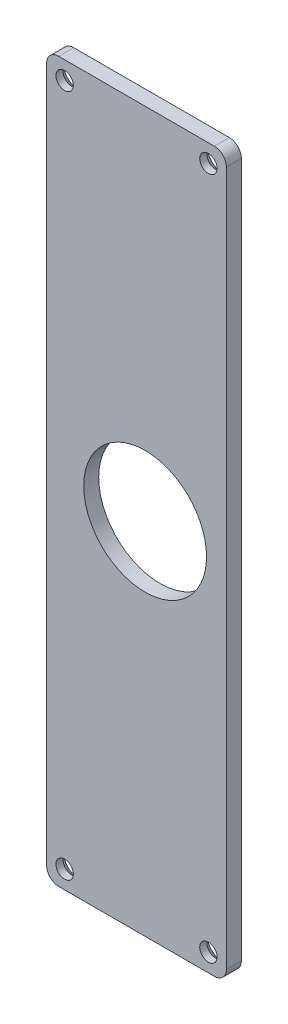
SolidWorks part; units mm, degrees
ref_plane "Front Plane" through (0, 0, 0) normal (0, 0, 1) x (1, 0, 0)
ref_plane "Top Plane" through (0, 0, 0) normal (0, 1, 0) x (1, 0, 0)
ref_plane "Right Plane" through (0, 0, 0) normal (1, 0, 0) x (0, 0, -1)
sketch "Sketch1" plane through (0, 0, 0) normal (0, 0, 1) x (1, 0, 0)
  line L0 (-63.1226, 90.4321) -> (-63.1226, -25.5679)
  line L1 (-91.1226, -27.5679) -> (-65.1226, -27.5679)
  line L2 (-93.1226, -25.5679) -> (-93.1226, 90.4321)
  line L3 (-91.1226, 92.4321) -> (-65.1226, 92.4321)
  arc A0 (-91.1226, -27.5679) -> (-93.1226, -25.5679) centre (-91.1226, -25.5679) cw
  arc A3 (-93.1226, 90.4321) -> (-91.1226, 92.4321) centre (-91.1226, 90.4321) cw
  arc A6 (-65.1226, 92.4321) -> (-63.1226, 90.4321) centre (-65.1226, 90.4321) cw
  arc A7 (-65.1226, -27.5679) -> (-63.1226, -25.5679) centre (-65.1226, -25.5679) ccw
  point P6 (-93.1226, -27.5679)
  point P23 (-63.1226, 92.4321)
  point P26 (-63.1226, -27.5679)
  dimension "D3" = 2
  dimension "D1" = 116
  dimension "D2" = 26
extrude "Boss-Extrude1" add sketch "Sketch1" along normal blind 2.5
hole_wizard "CSK for M2.5 Countersunk Flat Head Screw2" positions "3DSketch2" profile "Sketch3" countersink size "M2.5" standard "ISO" end condition through all
sketch3d "3DSketch2"
  line L0 (-65.1226, 92.4321, 0) -> (-91.1226, 92.4321, 0) construction
  line L2 (-93.1226, 90.4321, 0) -> (-93.1226, -25.5679, 0) construction
  line L4 (-91.1226, -27.5679, 0) -> (-65.1226, -27.5679, 0) construction
  line L5 (-63.1226, -25.5679, 0) -> (-63.1226, 90.4321, 0) construction
  point P0 (-66.1226, 89.4321, 0)
  point P2 (-90.1226, 89.4321, 0)
  point P4 (-66.1226, -24.5679, 0)
  point P6 (-90.1226, -24.5679, 0)
  dimension "D1" = 3
  dimension "D2" = 3
  dimension "D3" = 3
  dimension "D4" = 3
sketch "Sketch3" plane through (-66.1226, 89.4321, 0) normal (1, 0, 0) x (0, 1, 0)
  line L0 (0, 0) -> (0, 2.5)
  line L1 (0, 2.5) -> (1.45, 2.5)
  line L2 (1.45, 2.5) -> (1.45, 1.3)
  line L3 (1.45, 1.3) -> (2.75, 0)
  line L5 (2.75, 0) -> (0, 0)
  line L6 (-1.45, 1.3) -> (-2.75, 0) construction
  line L11 (0, -6.35) -> (0, 107.95) construction
  dimension "Thru Hole Dia." = 2.9
  dimension "Thru Hole Depth" = 2.5
  dimension "Near C'Sink Dia." = 5.5
  dimension "Near C'Sink Angle" = 90
sketch "Sketch4" plane through (0, 0, 0) normal (0, 0, -1) x (-1, 0, 0)
  line L0 (93.1226, 90.4321) -> (93.1226, -25.5679) construction
  line L1 (91.1226, -27.5679) -> (65.1226, -27.5679) construction
  circle A0 centre (76.6826, 32.4321) radius 10.25
  dimension "D2" = 20.5
  dimension "D1" = 16.44
  dimension "D3" = 60
extrude "Cut-Extrude1" cut sketch "Sketch4" against normal through all
